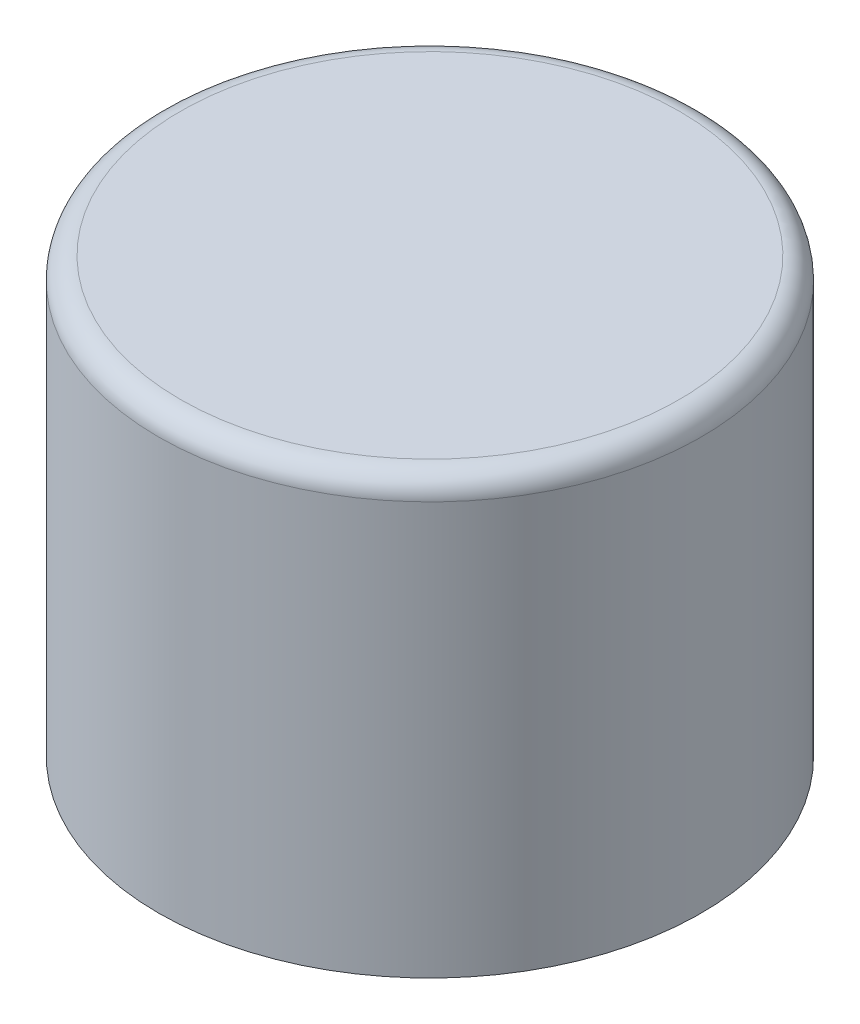
SolidWorks part; units mm, degrees
ref_plane "Front Plane" through (0, 0, 0) normal (0, 0, 1) x (1, 0, 0)
ref_plane "Top Plane" through (0, 0, 0) normal (0, 1, 0) x (1, 0, 0)
ref_plane "Right Plane" through (0, 0, 0) normal (1, 0, 0) x (0, 0, -1)
sketch "Sketch2" plane through (0, 0, 0) normal (0, 1, 0) x (1, 0, 0)
  circle A0 centre (0, 0) radius 31.75
  dimension "D1" = 63.5
extrude "Boss-Extrude2" add sketch "Sketch2" along normal blind 50.8
shell "Shell1" thickness 3.175
fillet "Fillet2" radius 2.54 1 edges at (0, 50.8, 31.75)
chamfer "Chamfer1" distance 2.54 angle 45 1 edges at (0, 0, 28.575)
